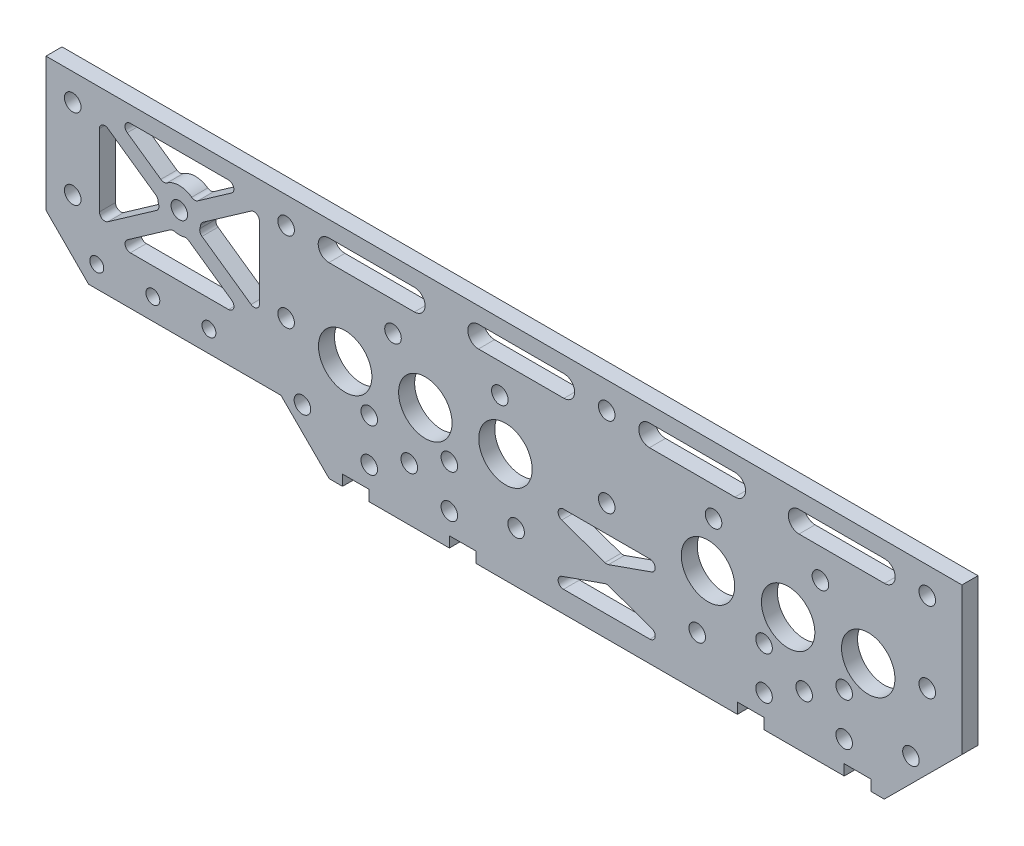
SolidWorks part; units mm, degrees
material "Thornel Mat VMA"
ref_plane "前视基准面" through (0, 0, 0) normal (0, 0, 1) x (1, 0, 0)
ref_plane "上视基准面" through (0, 0, 0) normal (0, 1, 0) x (1, 0, 0)
ref_plane "右视基准面" through (0, 0, 0) normal (1, 0, 0) x (0, 0, -1)
sketch "草图1" plane through (0, 0, 0) normal (0, 0, 1) x (1, 0, 0)
  line L0 (0, 7) -> (0, 0) construction
  line L1 (7.5, -4) -> (-7.5, -4) construction
  line L2 (7.5, -4) -> (7.5, 4) construction
  line L3 (7.5, 4) -> (-7.5, 4) construction
  line L4 (-7.5, -4) -> (-7.5, 4) construction
  line L5 (7.5, -4) -> (-7.5, 4) construction
  line L6 (7.5, 4) -> (-7.5, -4) construction
  line L7 (13.5, 4) -> (-13.5, 4) construction
  line L8 (13.5, 4) -> (13.5, 10) construction
  line L9 (13.5, 10) -> (-13.5, 10) construction
  line L10 (-13.5, 4) -> (-13.5, 10) construction
  line L11 (13.5, 4) -> (-13.5, 10) construction
  line L12 (13.5, 10) -> (-13.5, 4) construction
  line L13 (0, 0) -> (73.9, 0) construction
  line L14 (73.9, 7) -> (73.9, 0) construction
  line L15 (81.4, -4) -> (66.4, -4) construction
  line L16 (81.4, -4) -> (81.4, 4) construction
  line L17 (81.4, 4) -> (66.4, 4) construction
  line L18 (66.4, -4) -> (66.4, 4) construction
  line L19 (81.4, -4) -> (66.4, 4) construction
  line L20 (81.4, 4) -> (66.4, -4) construction
  line L21 (87.4, 4) -> (60.4, 4) construction
  line L22 (87.4, 4) -> (87.4, 10) construction
  line L23 (87.4, 10) -> (60.4, 10) construction
  line L24 (60.4, 4) -> (60.4, 10) construction
  line L25 (87.4, 4) -> (60.4, 10) construction
  line L26 (87.4, 10) -> (60.4, 4) construction
  line L27 (-68, 32) -> (103.45, 32)
  line L28 (86.4, -10) -> (-12.5, -10)
  line L30 (-68, 7) -> (-68, 32)
  line L31 (103.45, 32) -> (103.45, 7)
  line L33 (103.45, 7) -> (86.4, -10) construction
  line L34 (-63, 27) -> (-63, 12) construction
  line L35 (-68, 19.5) -> (-63, 19.5) construction
  line L36 (-63, 19.5) -> (96.95, 19.5) construction
  line L37 (36.95, -10) -> (36.95, 19.5) construction
  line L38 (-23.05, 27) -> (-23.05, 12) construction
  line L39 (36.95, 27) -> (36.95, 12) construction
  line L40 (96.95, 27) -> (96.95, 12) construction
  line L44 (-37.5, 3) -> (-58.5, 3) construction
  line L45 (-68, 7) -> (-60.0235, -1)
  line L52 (-15.05, 27) -> (0.95, 27) construction
  line L53 (-15.05, 29) -> (0.95, 29)
  line L54 (-15.05, 25) -> (0.95, 25)
  line L55 (12.95, 27) -> (28.95, 27) construction
  line L56 (12.95, 29) -> (28.95, 29)
  line L57 (12.95, 25) -> (28.95, 25)
  line L58 (44.95, 27) -> (60.95, 27) construction
  line L59 (44.95, 29) -> (60.95, 29)
  line L60 (44.95, 25) -> (60.95, 25)
  line L61 (72.95, 27) -> (88.95, 27) construction
  line L62 (72.95, 29) -> (88.95, 29)
  line L63 (72.95, 25) -> (88.95, 25)
  line L64 (-60.0235, -1) -> (-21.5265, -1) construction
  line L65 (-21.5265, -1) -> (-12.5, -10) construction
  line L66 (-58, 29) -> (-58, 8) construction
  line L67 (-58, 8) -> (-28.05, 8) construction
  line L68 (-28.05, 8) -> (-28.05, 29) construction
  line L69 (-28.05, 29) -> (-58, 29) construction
  line L70 (-30.6628, 29) -> (-40.2036, 22.3103)
  line L71 (-55.3872, 8) -> (-44.3708, 15.7244)
  line L72 (-55.3872, 29) -> (-45.8759, 22.331)
  line L73 (-58, 27.168) -> (-47.05, 19.4902)
  line L74 (-58, 29) -> (-28.05, 8) construction
  line L75 (-58, 8) -> (-28.05, 29) construction
  line L76 (-39.4254, 17.8081) -> (-28.05, 9.832)
  line L77 (-46.6621, 17.7817) -> (-58, 9.832)
  line L78 (-41.696, 15.7361) -> (-30.6628, 8)
  line L79 (-39.0503, 19.455) -> (-28.05, 27.168)
  line L80 (-55.3872, 29) -> (-30.6628, 29)
  line L81 (-58, 27.168) -> (-58, 9.832)
  line L82 (-55.3872, 8) -> (-30.6628, 8)
  line L83 (-28.05, 27.168) -> (-28.05, 9.832)
  line L84 (18.5, -4.4096) -> (32.4358, 0.5) construction
  line L85 (55.4, -6) -> (18.5, -6) construction
  line L86 (55.4, -6) -> (55.4, 7) construction
  line L87 (55.4, 7) -> (18.5, 7) construction
  line L88 (18.5, -6) -> (18.5, 7) construction
  line L89 (55.4, -6) -> (18.5, 7) construction
  line L90 (55.4, 7) -> (18.5, -6) construction
  line L91 (23.0142, -6) -> (36.95, -1.0904)
  line L92 (23.0142, 7) -> (36.95, 2.0904)
  line L93 (18.5, 5.4096) -> (32.4358, 0.5) construction
  line L94 (36.95, 2.0904) -> (50.8858, 7)
  line L95 (41.4642, 0.5) -> (55.4, -4.4096) construction
  line L96 (41.4642, 0.5) -> (55.4, 5.4096) construction
  line L97 (36.95, -1.0904) -> (50.8858, -6)
  line L98 (18.5, 5.4096) -> (18.5, -4.4096) construction
  line L99 (23.0142, -6) -> (50.8858, -6)
  line L100 (55.4, -4.4096) -> (55.4, 5.4096) construction
  line L101 (50.8858, 7) -> (23.0142, 7)
  line L102 (103.45, 7) -> (103.45, 4.5)
  line L103 (103.45, 4.5) -> (88.9074, -10)
  line L104 (88.9074, -10) -> (86.4, -10)
  line L105 (-60.0235, -1) -> (-24.0265, -1)
  line L106 (-24.0265, -1) -> (-15, -10)
  line L107 (-15, -10) -> (-12.5, -10)
  circle A0 centre (-7.5, 4) radius 1.55
  circle A1 centre (-7.5, -4) radius 1.55
  circle A2 centre (7.5, -4) radius 1.55
  circle A3 centre (7.5, 4) radius 1.55
  circle A4 centre (66.4, 4) radius 1.55
  circle A5 centre (66.4, -4) radius 1.55
  circle A6 centre (81.4, 4) radius 1.55
  circle A7 centre (81.4, -4) radius 1.55
  circle A8 centre (-63, 27) radius 1.55
  circle A9 centre (-63, 12) radius 1.55
  circle A10 centre (36.95, 19.5) radius 1.55 construction
  circle A11 centre (16.95, 19.5) radius 1.55
  circle A12 centre (-3.05, 19.5) radius 1.55
  circle A15 centre (-23.05, 27) radius 1.55
  circle A16 centre (-23.05, 12) radius 1.55
  circle A17 centre (36.95, 27) radius 1.55
  circle A18 centre (36.95, 12) radius 1.55
  circle A19 centre (56.95, 19.5) radius 1.55
  circle A20 centre (76.95, 19.5) radius 1.55
  circle A21 centre (-23.05, 19.5) radius 1.55 construction
  circle A22 centre (-43.05, 19.5) radius 1.55 [skipped]
  circle A24 centre (96.95, 27) radius 1.55
  circle A25 centre (96.95, 12) radius 1.55
  arc A31 (-15.05, 29) -> (-15.05, 25) centre (-15.05, 27) ccw
  arc A32 (0.95, 25) -> (0.95, 29) centre (0.95, 27) ccw
  arc A33 (12.95, 29) -> (12.95, 25) centre (12.95, 27) ccw
  arc A34 (28.95, 25) -> (28.95, 29) centre (28.95, 27) ccw
  arc A35 (44.95, 29) -> (44.95, 25) centre (44.95, 27) ccw
  arc A36 (60.95, 25) -> (60.95, 29) centre (60.95, 27) ccw
  arc A37 (72.95, 29) -> (72.95, 25) centre (72.95, 27) ccw
  arc A38 (88.95, 25) -> (88.95, 29) centre (88.95, 27) ccw
  circle A39 centre (-48, 3) radius 1.3
  circle A40 centre (-37.5, 3) radius 1.3
  circle A41 centre (-58.5, 3) radius 1.3
  circle A42 centre (-43.05, 19.5) radius 1.55
  arc A43 (-44.3708, 15.7244) -> (-41.696, 15.7361) centre (-43.05, 19.5) ccw
  arc A44 (-47.05, 19.4902) -> (-46.6621, 17.7817) centre (-43.05, 19.5) ccw
  arc A45 (-40.2036, 22.3103) -> (-45.8759, 22.331) centre (-43.05, 19.5) ccw
  arc A46 (-39.4254, 17.8081) -> (-39.0503, 19.455) centre (-43.05, 19.5) ccw
  circle A47 centre (93.9, -0.5) radius 1.55
  circle A48 centre (53.9, -0.5) radius 1.55
  circle A49 centre (-20, -0.5) radius 1.55
  circle A50 centre (20, -0.5) radius 1.55
  point P0 (0, 0)
  point P10 (0, 7)
  point P22 (73.9, 7)
  point P83 (36.95, 0.5)
  point P87 (-7.05, 27)
  point P94 (20.95, 27)
  point P101 (52.95, 27)
  point P108 (80.95, 27)
  dimension "D1" = 3.1
  dimension "D16" = 15
  dimension "D24" = 21
  dimension "D27" = 2
  dimension "D26" = 2.6
  dimension "D42" = 8
  dimension "D50" = 3.1
  dimension "D2" = 15
  dimension "D3" = 8
  dimension "D4" = 6
  dimension "D5" = 3
  dimension "D6" = 27
  dimension "D7" = 73.9
  dimension "D8" = 20
  dimension "D9" = 55.5
  dimension "D10" = 6
  dimension "D11" = 25
  dimension "D12" = 12.5
  dimension "D13" = 12.5
  dimension "D14" = 25
  dimension "D15" = 5
  dimension "D18" = 20
  dimension "D20" = 20
  dimension "D21" = 20
  dimension "D22" = 4
  dimension "D23" = 6.5
  dimension "D25" = 25
  dimension "D28" = 3
  dimension "D29" = 16
  dimension "D30" = 16
  dimension "D31" = 16
  dimension "D32" = 16
  dimension "D33" = 16
  dimension "D34" = 20
  dimension "D35" = 4
  dimension "D36" = 5
  dimension "D37" = 5
  dimension "D38" = 5
  dimension "D39" = 3
  dimension "D40" = 3
  dimension "D41" = 3
  dimension "D43" = 5
  dimension "D44" = 5
  dimension "D45" = 4
  dimension "D46" = 2.5
  dimension "D47" = 3
  dimension "D48" = 7.5
  dimension "D49" = 7.5
  dimension "D51" = 2.5
  dimension "D17" = 5
  dimension "D19" = 3
extrude "凸台-拉伸1" add sketch "草图1" along normal blind 3
fillet "圆角1" radius 1 22 edges at (23.0142, 7, 1.5) (36.95, 2.0904, 1.5) (50.8858, 7, 1.5) (-28.05, 27.168, 1.5) (-39.0503, 19.455, 1.5) (-39.4254, 17.8081, 1.5) (-28.05, 9.832, 1.5) (-30.6628, 8, 1.5) (-41.696, 15.7361, 1.5) (-44.3708, 15.7244, 1.5) (-55.3872, 8, 1.5) (-55.3872, 29, 1.5) (-45.8759, 22.331, 1.5) (-40.2036, 22.3103, 1.5) (-30.6628, 29, 1.5) (-58, 9.832, 1.5) (-46.6621, 17.7817, 1.5) (-47.05, 19.4902, 1.5) (-58, 27.168, 1.5) (50.8858, -6, 1.5) (36.95, -1.0904, 1.5) (23.0142, -6, 1.5)
sketch "草图2" plane through (0, 0, 3) normal (0, 0, 1) x (1, 0, 0)
  line L0 (36.9537, -10) -> (36.9537, -26.9066) construction
  line L1 (-15, -10) -> (88.9074, -10) construction
  circle A0 centre (-12, 10.5) radius 5
  circle A1 centre (3, 10.5) radius 5
  circle A2 centre (18, 10.5) radius 5
  circle A3 centre (55.9074, 10.5) radius 5
  circle A4 centre (70.9074, 10.5) radius 5
  circle A5 centre (85.9074, 10.5) radius 5
  circle A6 centre (-3.05, 19.5) radius 1.55 construction
  circle A7 centre (0, 0) radius 1.55
  circle A8 centre (73.9074, 0) radius 1.55
  dimension "D1" = 10
  dimension "D6" = 3.1
  dimension "D2" = 12
  dimension "D3" = 15
  dimension "D4" = 15
  dimension "D5" = 9
extrude "切除-拉伸1" cut sketch "草图2" against normal blind 10
sketch "草图3" plane through (0, 0, 3) normal (0, 0, 1) x (1, 0, 0)
  line L0 (0, 0) -> (0, -17.9622) construction
  line L1 (-7.5, -16) -> (-12.5, -16)
  line L2 (-7.5, -16) -> (-7.5, -8)
  line L3 (-7.5, -8) -> (-12.5, -8)
  line L4 (-12.5, -16) -> (-12.5, -8)
  line L5 (-7.5, -16) -> (-12.5, -8) construction
  line L6 (-7.5, -8) -> (-12.5, -16) construction
  line L7 (7.5, -8) -> (12.5, -8)
  line L8 (12.5, -16) -> (12.5, -8)
  line L9 (7.5, -16) -> (12.5, -16)
  line L10 (7.5, -16) -> (7.5, -8)
  line L11 (10, -8) -> (10, -16) construction
  line L12 (-15, -10) -> (88.9074, -10) construction
  line L13 (36.9537, -10) -> (36.9537, -20.6571) construction
  line L14 (66.4074, -16) -> (66.4074, -8)
  line L15 (66.4074, -16) -> (61.4074, -16)
  line L16 (61.4074, -16) -> (61.4074, -8)
  line L17 (66.4074, -8) -> (61.4074, -8)
  line L18 (81.4074, -8) -> (86.4074, -8)
  line L19 (86.4074, -16) -> (86.4074, -8)
  line L20 (81.4074, -16) -> (86.4074, -16)
  line L21 (81.4074, -16) -> (81.4074, -8)
  point P0 (-10, -12)
  dimension "D1" = 20
  dimension "D2" = 5
  dimension "D3" = 8
  dimension "D4" = 2
extrude "切除-拉伸2" cut sketch "草图3" against normal blind 10
